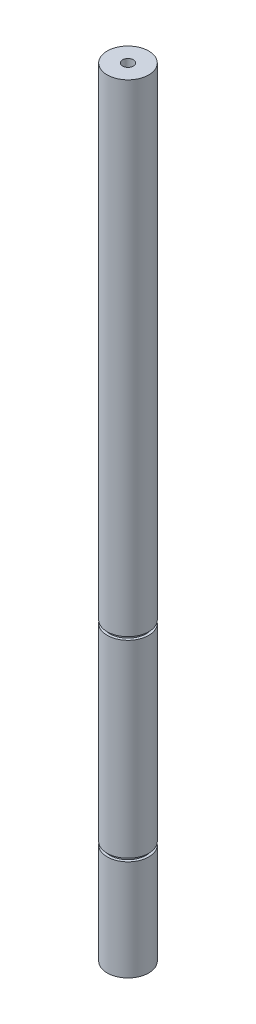
SolidWorks part; units mm, degrees
material "1060 合金"
ref_plane "前视基准面" through (0, 0, 0) normal (0, 0, 1) x (1, 0, 0)
ref_plane "上视基准面" through (0, 0, 0) normal (0, 1, 0) x (1, 0, 0)
ref_plane "右视基准面" through (0, 0, 0) normal (1, 0, 0) x (0, 0, -1)
sketch "草图1" plane through (0, 0, 0) normal (0, 1, 0) x (1, 0, 0)
  circle A0 centre (0, 0) radius 8
  dimension "D1" = 16
extrude "凸台-拉伸1" add sketch "草图1" along normal mid plane 300
sketch "草图2" plane through (0, 150, 0) normal (0, 1, 0) x (1, 0, 0)
  circle A0 centre (0, 0) radius 5
  dimension "D1" = 10
extrude "切除-拉伸1" [suppressed] cut sketch "草图2" against normal through all
hole_wizard "M5 螺纹孔1" positions "草图4" profile "草图3" tap size "M5" standard "GB"
sketch "草图4" plane through (0, 150, 0) normal (0, 1, 0) x (1, 0, 0)
  point P0 (0, 0)
sketch "草图3" plane through (0, 150, 0) normal (1, 0, 0) x (0, 0, 1)
  line L0 (0, 0) -> (0, 15.2618)
  line L1 (0, 15.2618) -> (2.1, 14)
  line L2 (2.1, 14) -> (2.1, 0)
  line L5 (2.1, 0) -> (0, 0)
  line L10 (0, 15.2618) -> (-2.1, 14) construction
  line L11 (0, -6.35) -> (0, 107.95) construction
  dimension "螺纹孔钻头直径" = 4.2
  dimension "螺纹孔钻头深度" = 14
  dimension "导头角度" = 118
cosmetic thread "孔螺蚊线1"
mirror "镜向1" about plane through (0, 0, 0) normal (0, 1, 0) of "M5 螺纹孔1"
sketch "草图5" plane through (0, 0, 0) normal (0, 0, 1) x (1, 0, 0)
  line L0 (8, -150) -> (8, 150) construction
  line L1 (8, -110) -> (7, -110)
  line L2 (8, -110) -> (8, -111.2)
  line L3 (8, -111.2) -> (7, -111.2)
  line L4 (7, -110) -> (7, -111.2)
  line L6 (-8, -150) -> (8, -150) construction
  dimension "D1" = 40
  dimension "D2" = 1.2
  dimension "D3" = 1
revolve "切除-旋转1" cut sketch "草图5" angle 360 about axis through (0, 150, 0) along (0, -1, 0)
pattern_linear "阵列(线性)1" count 2 spacing 74 along (0, 1, 0) of "切除-旋转1"
